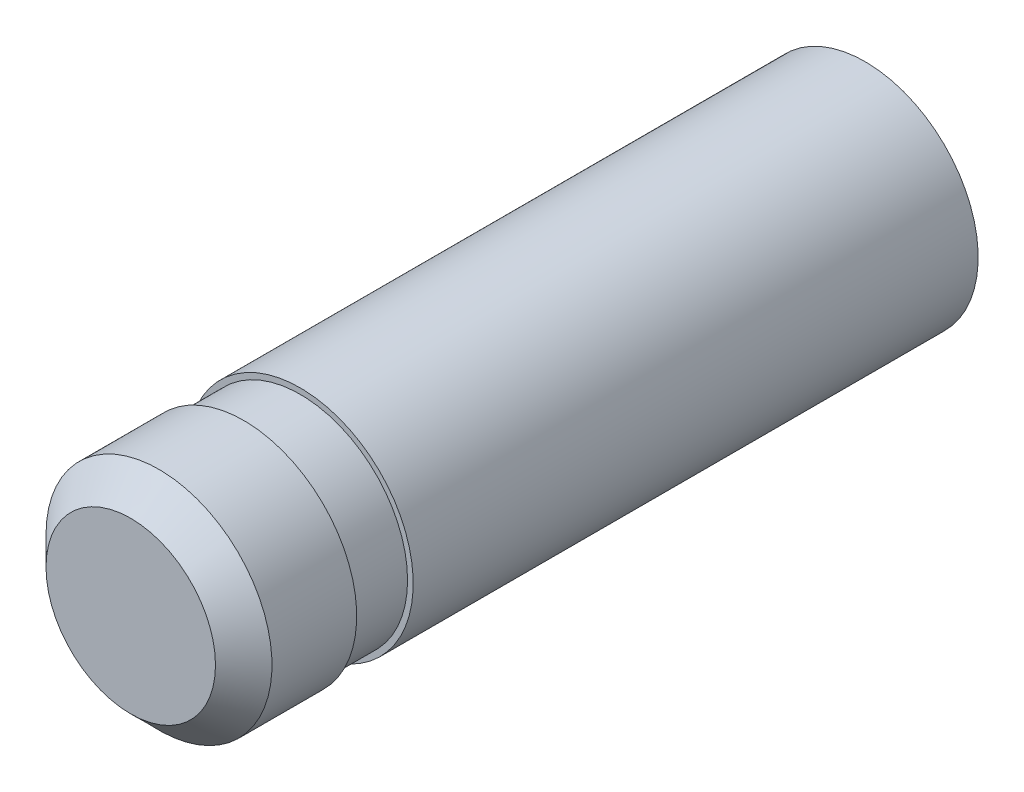
SolidWorks part; units mm, degrees
ref_plane "Front Plane" through (0, 0, 0) normal (0, 0, 1) x (1, 0, 0)
ref_plane "Top Plane" through (0, 0, 0) normal (0, 1, 0) x (1, 0, 0)
ref_plane "Right Plane" through (0, 0, 0) normal (1, 0, 0) x (0, 0, -1)
sketch "Sketch1" plane through (0, 0, 0) normal (0, 0, 1) x (1, 0, 0)
  circle A0 centre (0, 0) radius 2
  dimension "4" = 4
extrude "Boss-Extrude1" add sketch "Sketch1" along normal blind 13
sketch "Sketch2" plane through (0, 0, 0) normal (0, 0, -1) x (-1, 0, 0)
  circle A0 centre (0, 0) radius 1.9
  dimension "D1" = 3.8
extrude "Cut-Extrude1" cut sketch "Sketch2" against normal blind 1 from offset 10 flip side to cut offset against normal yes
chamfer "Chamfer1" distance 0.5 angle 45 1 edges at (2, 0, 13)
